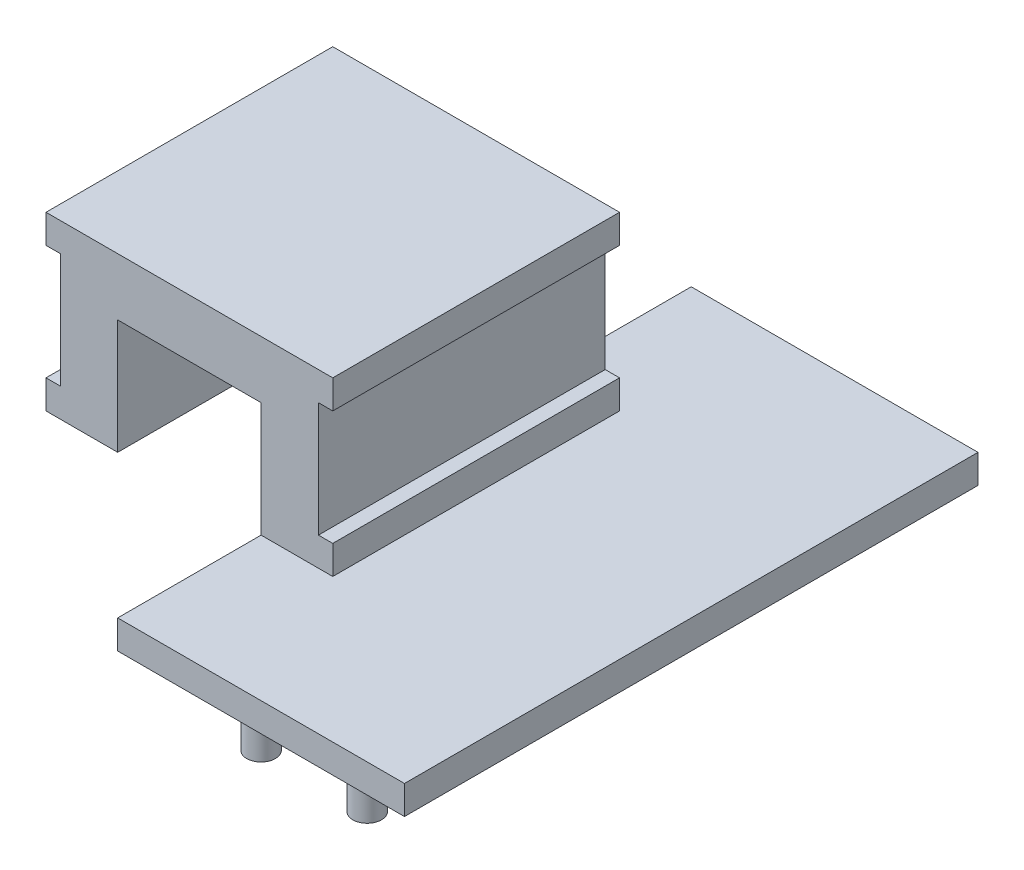
SolidWorks part; units mm, degrees
ref_plane "Front Plane" through (0, 0, 0) normal (0, 0, 1) x (1, 0, 0)
ref_plane "Top Plane" through (0, 0, 0) normal (0, 1, 0) x (1, 0, 0)
ref_plane "Right Plane" through (0, 0, 0) normal (1, 0, 0) x (0, 0, -1)
sketch "Sketch1" plane through (0, 0, 0) normal (0, 1, 0) x (1, 0, 0)
  line L1 (-12.7, -12.7) -> (12.7, -12.7)
  line L2 (-12.7, -12.7) -> (-12.7, 12.7)
  line L3 (-12.7, 12.7) -> (12.7, 12.7)
  line L4 (12.7, -12.7) -> (12.7, 12.7)
  line L5 (-12.7, -12.7) -> (12.7, 12.7) construction
  line L6 (-12.7, 12.7) -> (12.7, -12.7) construction
  point P0 (0, 0)
  dimension "D1" = 25.4
  dimension "D2" = 25.4
extrude "Boss-Extrude1" add sketch "Sketch1" along normal blind 15.24
sketch "Sketch2" plane through (0, 0, 0) normal (0, -1, 0) x (1, 0, 0)
  line L0 (-12.7, 12.7) -> (12.7, 12.7) construction
  line L1 (-6.35, 12.7) -> (6.35, 12.7)
  line L2 (-6.35, 12.7) -> (-6.35, -12.7)
  line L3 (-6.35, -12.7) -> (6.35, -12.7)
  line L4 (6.35, 12.7) -> (6.35, -12.7)
  line L5 (12.7, -12.7) -> (-12.7, -12.7) construction
  line L6 (0, 12.7) -> (0, 0) construction
  point P8 (0, 12.7)
  dimension "D1" = 12.7
extrude "Cut-Extrude1" cut sketch "Sketch2" against normal blind 10.16
sketch "Sketch3" plane through (0, 0, 12.7) normal (0, 0, 1) x (1, 0, 0)
  line L0 (-12.7, 15.24) -> (-12.7, 0) construction
  line L1 (-12.7, 12.7) -> (-11.43, 12.7)
  line L2 (-12.7, 12.7) -> (-12.7, 2.54)
  line L3 (-12.7, 2.54) -> (-11.43, 2.54)
  line L4 (-11.43, 12.7) -> (-11.43, 2.54)
  line L5 (12.7, 15.24) -> (12.7, 0) construction
  line L6 (12.7, 12.7) -> (11.43, 12.7)
  line L7 (12.7, 12.7) -> (12.7, 2.54)
  line L8 (12.7, 2.54) -> (11.43, 2.54)
  line L9 (11.43, 12.7) -> (11.43, 2.54)
  line L10 (6.35, 10.16) -> (-6.35, 10.16) construction
  dimension "D1" = 1.27
  dimension "D2" = 10.16
  dimension "D3" = 2.54
extrude "Cut-Extrude2" cut sketch "Sketch3" against normal through all
sketch "Sketch4" plane through (0, 0, 0) normal (0, -1, 0) x (1, 0, 0)
  line L0 (6.35, -12.7) -> (6.35, 12.7) construction
  line L1 (6.35, -25.4) -> (31.75, -25.4)
  line L2 (6.35, -25.4) -> (6.35, 25.4)
  line L3 (6.35, 25.4) -> (31.75, 25.4)
  line L4 (31.75, -25.4) -> (31.75, 25.4)
  point P4 (6.35, 0)
  point P5 (6.35, 0)
  point P8 (6.35, 0)
  dimension "D1" = 25.4
  dimension "D2" = 50.8
extrude "Boss-Extrude2" add sketch "Sketch4" along normal blind 2.54
sketch "Sketch5" plane through (0, -2.54, 0) normal (0, -1, 0) x (1, 0, 0)
  line L0 (12.7, 19.05) -> (22.098, 19.05) construction
  line L1 (22.098, 19.05) -> (22.098, -19.05) construction
  line L2 (22.098, -19.05) -> (12.7, -19.05) construction
  line L3 (12.7, -19.05) -> (12.7, 19.05) construction
  line L4 (31.75, 25.4) -> (6.35, 25.4) construction
  line L5 (6.35, 25.4) -> (6.35, -25.4) construction
  line L6 (6.35, -25.4) -> (31.75, -25.4) construction
  circle A0 centre (12.7, 19.05) radius 1.27
  circle A1 centre (22.098, 19.05) radius 1.27
  circle A2 centre (12.7, -19.05) radius 1.27
  circle A3 centre (22.098, -19.05) radius 1.27
  dimension "D1" = 2.54
  dimension "D2" = 9.398
  dimension "D3" = 6.35
  dimension "D4" = 6.35
  dimension "D5" = 6.35
extrude "Boss-Extrude3" add sketch "Sketch5" along normal blind 7.62
